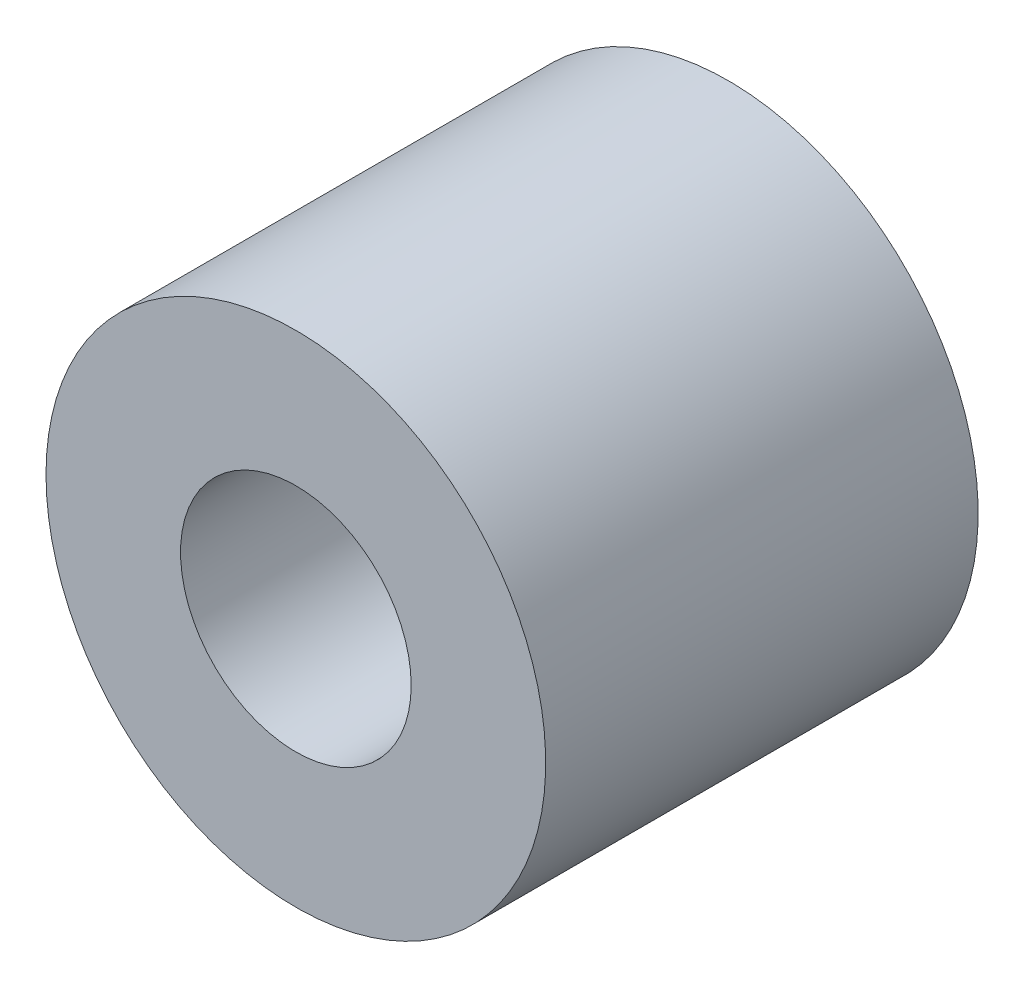
SolidWorks part; units mm, degrees
material "Polyester Resin"
ref_plane "Front Plane" through (0, 0, 0) normal (0, 0, 1) x (1, 0, 0)
ref_plane "Top Plane" through (0, 0, 0) normal (0, 1, 0) x (1, 0, 0)
ref_plane "Right Plane" through (0, 0, 0) normal (1, 0, 0) x (0, 0, -1)
sketch "Sketch1" plane through (0, 0, 0) normal (0, 0, 1) x (1, 0, 0)
  circle A0 centre (0, 0) radius 26
  dimension "D1" = 52
extrude "Boss-Extrude1" add sketch "Sketch1" along normal blind 45
sketch "Sketch2" plane through (0, 0, 45) normal (0, 0, 1) x (1, 0, 0)
  circle A0 centre (0, 0) radius 12
  dimension "D1" = 24
extrude "Cut-Extrude1" cut sketch "Sketch2" against normal through all
